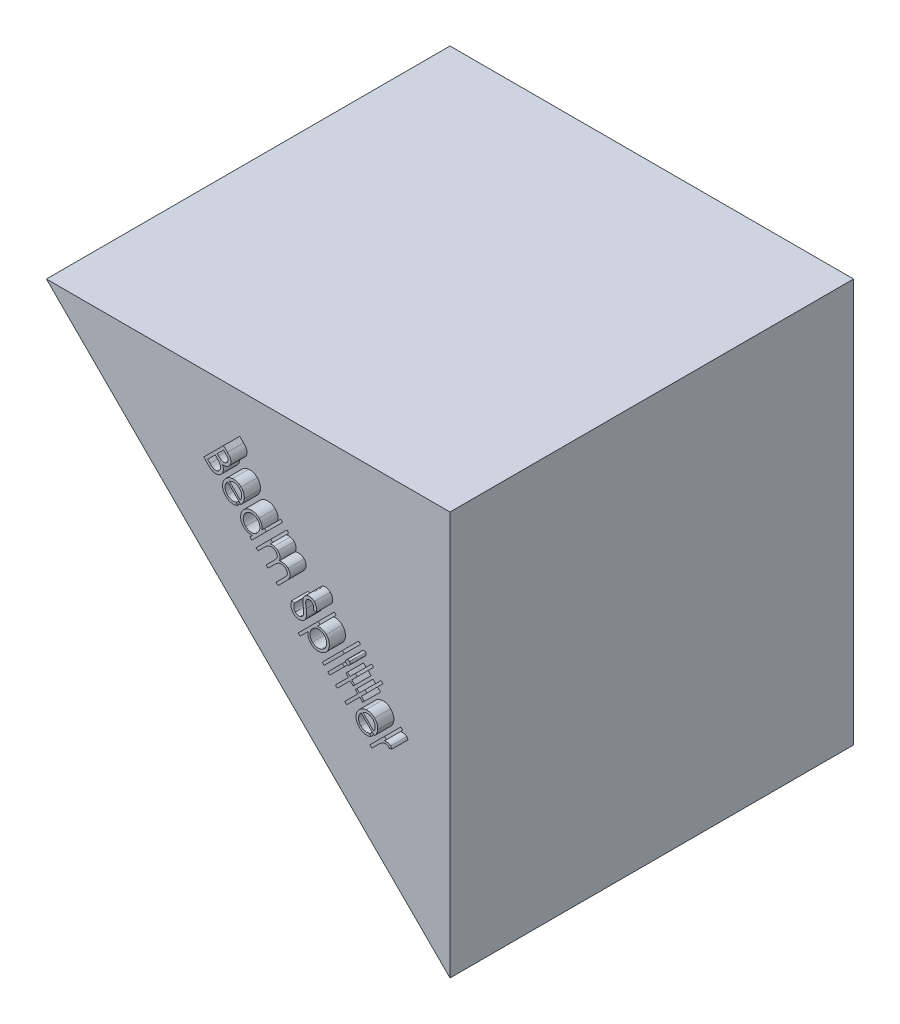
SolidWorks part; units mm, degrees
ref_plane "Front Plane" through (0, 0, 0) normal (0, 0, 1) x (1, 0, 0)
ref_plane "Top Plane" through (0, 0, 0) normal (0, 1, 0) x (1, 0, 0)
ref_plane "Right Plane" through (0, 0, 0) normal (1, 0, 0) x (0, 0, -1)
sketch "Sketch2" plane through (0, 0, 0) normal (0, 0, 1) x (1, 0, 0)
  line L0 (0, 35.7332) -> (0, -35.7332) construction
  line L1 (-57.8326, 0) -> (57.8326, 0) construction
  line L2 (-25, 25) -> (25, -25)
  line L3 (-25, 25) -> (25, 25)
  line L4 (25, 25) -> (25, -25)
  point P4 (0, 0)
  point P8 (0, 0)
  point P11 (0, 0)
  dimension "D1" = 45
  dimension "D2" = 50
extrude "Boss-Extrude1" add sketch "Sketch2" along normal blind 50
sketch "Sketch4" plane through (0, 0, 50) normal (0, 0, 1) x (1, 0, 0)
  line L0 (25, -10.8579) -> (-10.8579, 25) construction
  line L1 (25, -25) -> (25, 25) construction
  line L2 (25, 25) -> (-25, 25) construction
  line L3 (-25, 25) -> (25, -25) construction
  text T0 "Beam Splitter"
  dimension "D1" = 10
extrude "Boss-Extrude2" add sketch "Sketch4" along normal blind 2
